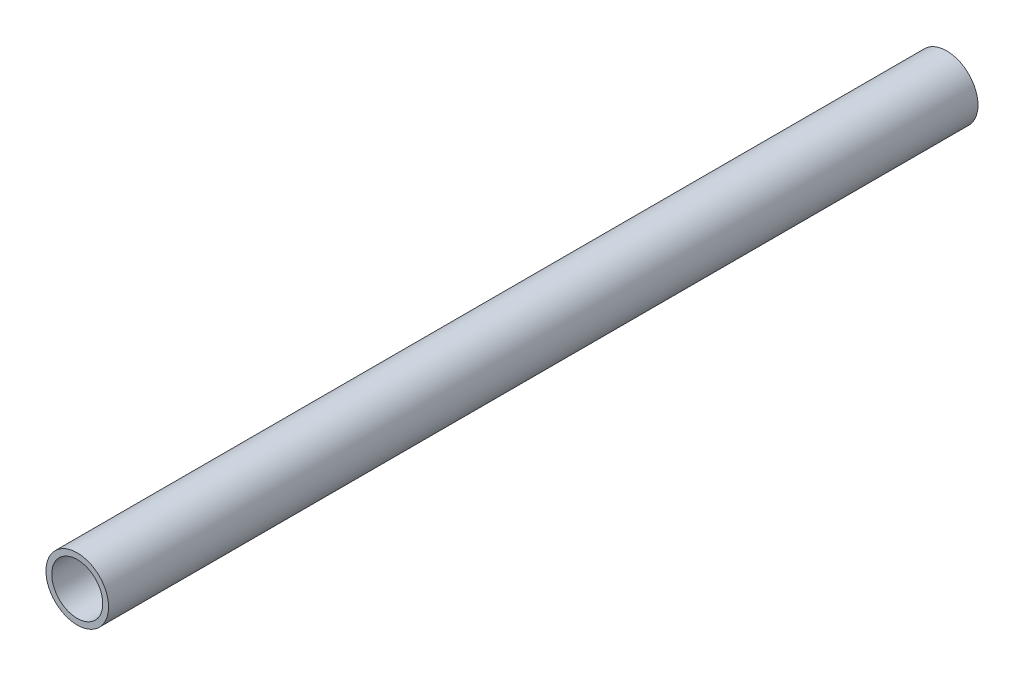
SolidWorks part; units mm, degrees
ref_plane "Alzado" through (0, 0, 0) normal (0, 0, 1) x (1, 0, 0)
ref_plane "Planta" through (0, 0, 0) normal (0, 1, 0) x (1, 0, 0)
ref_plane "Vista lateral" through (0, 0, 0) normal (1, 0, 0) x (0, 0, -1)
sketch "Croquis1" plane through (0, 0, 0) normal (0, 0, 1) x (1, 0, 0)
  circle A0 centre (0, 0) radius 10.8
  circle A1 centre (0, 0) radius 8.8
  dimension "D1" = 21.6
  dimension "D2" = 2
extrude "Saliente-Extruir1" add sketch "Croquis1" along normal blind 300
